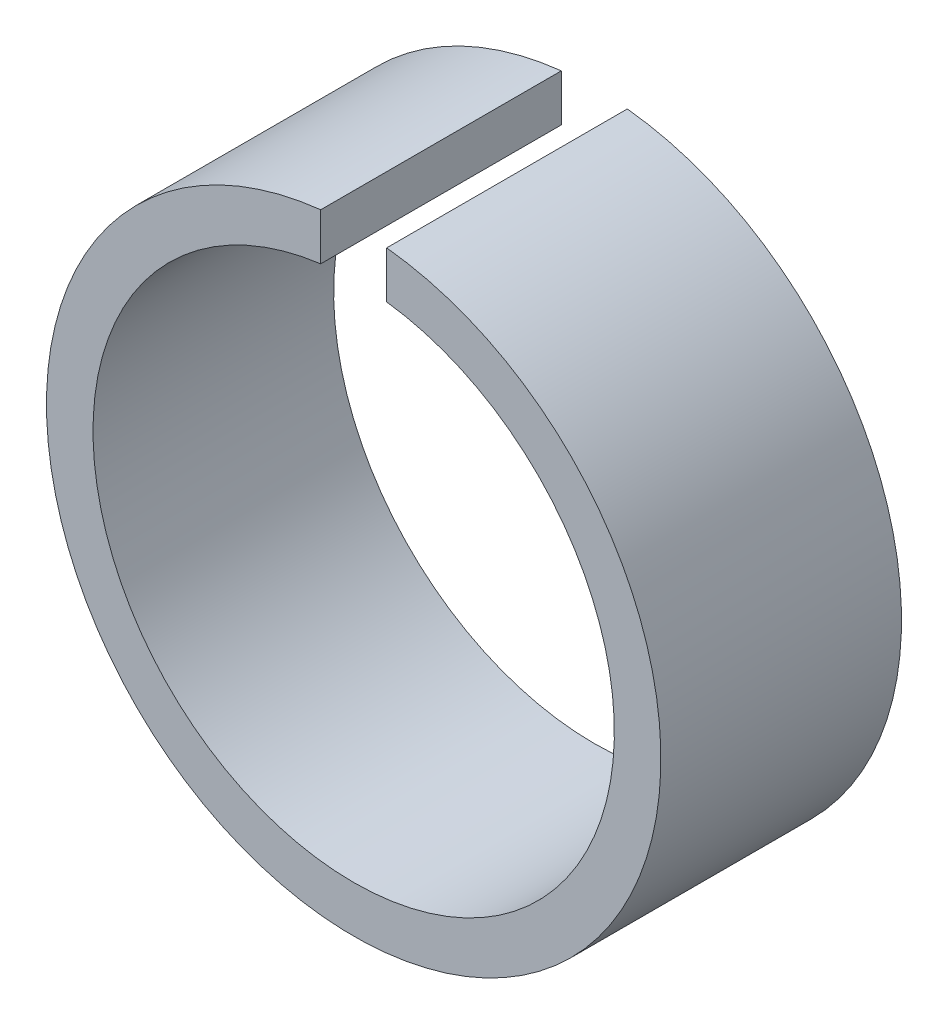
SolidWorks part; units mm, degrees
ref_plane "Front Plane" through (0, 0, 0) normal (0, 0, 1) x (1, 0, 0)
ref_plane "Top Plane" through (0, 0, 0) normal (0, 1, 0) x (1, 0, 0)
ref_plane "Right Plane" through (0, 0, 0) normal (1, 0, 0) x (0, 0, -1)
sketch "Sketch1" plane through (0, 0, 0) normal (0, 0, 1) x (1, 0, 0)
  line L0 (-2.612, 24.1798) -> (-2.612, 20.4715)
  line L1 (-2.612, -33.0857) -> (2.612, -33.0857) construction
  line L2 (-2.612, -33.0857) -> (-2.612, 33.0857) construction
  line L3 (-2.612, 33.0857) -> (2.612, 33.0857) construction
  line L4 (2.612, -33.0857) -> (2.612, 33.0857) construction
  line L5 (-2.612, -33.0857) -> (2.612, 33.0857) construction
  line L6 (-2.612, 33.0857) -> (2.612, -33.0857) construction
  line L7 (2.612, 24.1798) -> (2.612, 20.4715)
  arc A0 (-2.612, 20.4715) -> (2.612, 20.4715) centre (0, 0) ccw
  arc A1 (-2.612, 24.1798) -> (2.612, 24.1798) centre (0, 0) ccw
  circle A2 centre (0, 0) radius 24.3205 construction
  circle A3 centre (0, 0) radius 20.6375 construction
  dimension "D1" = 3.683
  dimension "D2" = 5.2241
extrude "Boss-Extrude1" add sketch "Sketch1" along normal blind 19.05
